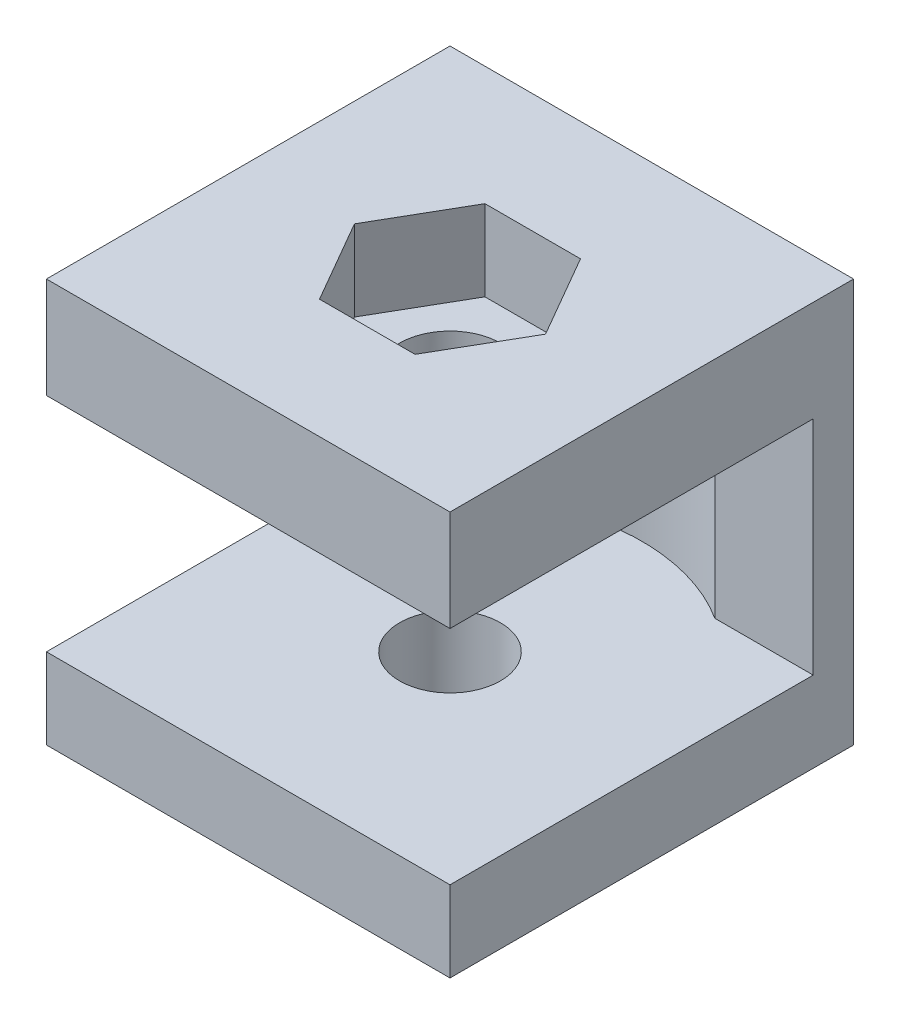
SolidWorks part; units mm, degrees
ref_plane "Płaszczyzna przednia" through (0, 0, 0) normal (0, 0, 1) x (1, 0, 0)
ref_plane "Płaszczyzna górna" through (0, 0, 0) normal (0, 1, 0) x (1, 0, 0)
ref_plane "Płaszczyzna prawa" through (0, 0, 0) normal (1, 0, 0) x (0, 0, -1)
sketch "Szkic1" plane through (0, 0, 0) normal (0, 0, 1) x (1, 0, 0)
  line L1 (-10, -10) -> (10, -10)
  line L2 (-10, -10) -> (-10, 10)
  line L3 (-10, 10) -> (10, 10)
  line L4 (10, -10) -> (10, 10)
  line L5 (-10, -10) -> (10, 10) construction
  line L6 (-10, 10) -> (10, -10) construction
  point P0 (0, 0)
  dimension "D1" = 20
  dimension "D2" = 20
extrude "Dodanie-wyciągnięcie1" add sketch "Szkic1" along normal blind 2
sketch "Szkic2" plane through (0, 0, 2) normal (0, 0, 1) x (1, 0, 0)
  circle A0 centre (0, 0) radius 1.75
  dimension "D1" = 3.5
extrude "Wytnij-wyciągnięcie1" cut sketch "Szkic2" against normal through all
sketch "Szkic3" plane through (0, 0, 2) normal (0, 0, 1) x (1, 0, 0)
  line L0 (10, -10) -> (10, 10) construction
  line L1 (-10, 10) -> (10, 10)
  line L2 (-10, 10) -> (-10, 5)
  line L3 (-10, 5) -> (10, 5)
  line L4 (10, 10) -> (10, 5)
  line L5 (-10, 10) -> (-10, -10) construction
  line L6 (10, -10) -> (-10, -10)
  line L7 (10, -10) -> (10, -6)
  line L8 (10, -6) -> (-10, -6)
  line L9 (-10, -10) -> (-10, -6)
  dimension "D1" = 5
  dimension "D2" = 4
extrude "Dodanie-wyciągnięcie2" add sketch "Szkic3" along normal blind 18
sketch "Szkic4" plane through (0, 10, 0) normal (0, 1, 0) x (1, 0, 0)
  line L1 (10, 0) -> (-10, 0) construction
  circle A0 centre (0, -10) radius 2.5
  point P6 (0, 0)
  point P7 (0, -12.124)
  dimension "D1" = 5
  dimension "D2" = 10
extrude "Wytnij-wyciągnięcie2" cut sketch "Szkic4" against normal through all
sketch "Szkic6" plane through (0, 10, 0) normal (0, 1, 0) x (1, 0, 0)
  line L1 (4.7343, -10) -> (2.3671, -5.9)
  line L2 (2.3671, -5.9) -> (-2.3671, -5.9)
  line L3 (-2.3671, -5.9) -> (-4.7343, -10)
  line L4 (-4.7343, -10) -> (-2.3671, -14.1)
  line L5 (-2.3671, -14.1) -> (2.3671, -14.1)
  line L6 (2.3671, -14.1) -> (4.7343, -10)
  circle A0 centre (0, -10) radius 4.1 construction
  point P1 (0, 0)
  dimension "D1" = 8.2
extrude "Wytnij-wyciągnięcie3" cut sketch "Szkic6" against normal blind 4
sketch "Szkic7" plane through (0, -10, 0) normal (0, -1, 0) x (1, 0, 0)
  circle A0 centre (0, 10) radius 9.5
  dimension "D1" = 19
extrude "Wytnij-wyciągnięcie5" cut sketch "Szkic7" against normal blind 11 from offset 4
